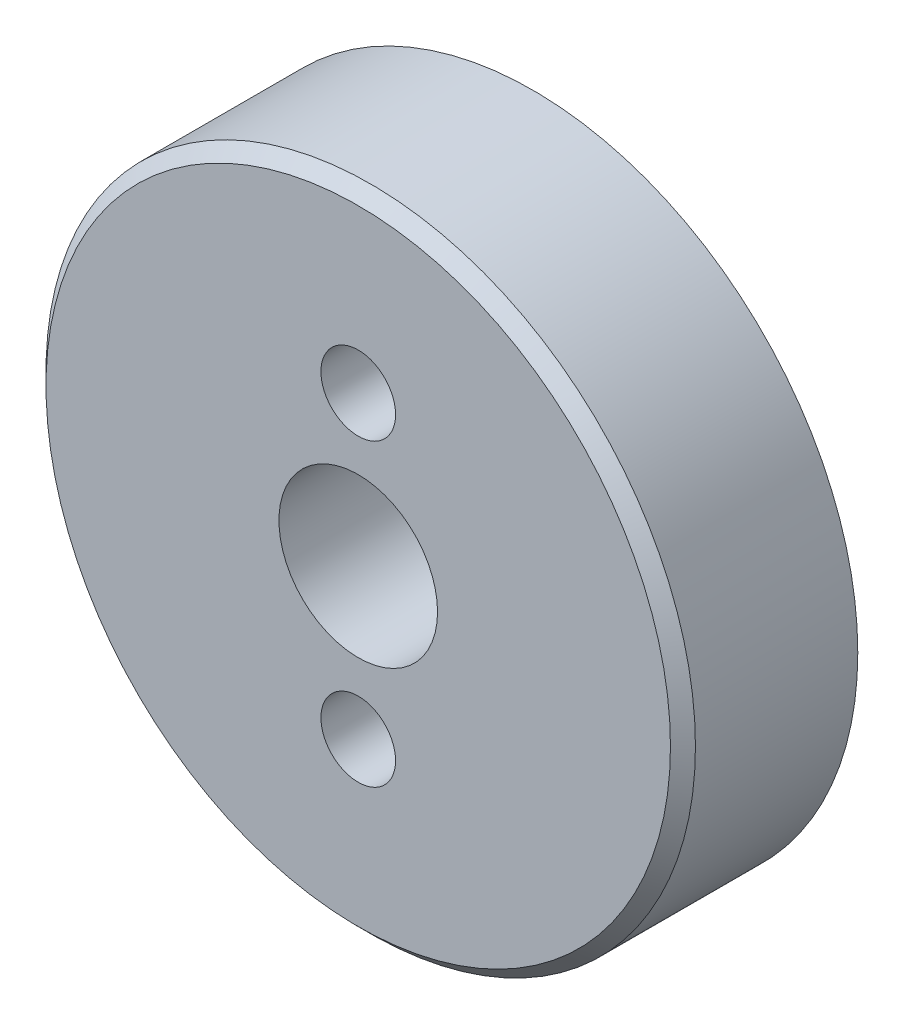
SolidWorks part; units mm, degrees
ref_plane "Спереди" through (0, 0, 0) normal (0, 0, 1) x (1, 0, 0)
ref_plane "Сверху" through (0, 0, 0) normal (0, 1, 0) x (1, 0, 0)
ref_plane "Справа" through (0, 0, 0) normal (1, 0, 0) x (0, 0, -1)
sketch "Эскиз1" plane through (0, 0, 0) normal (0, 0, 1) x (1, 0, 0)
  circle A0 centre (0, 0) radius 13
  circle A1 centre (0, 0) radius 3.175
  circle A2 centre (0, 6) radius 1.4944
  circle A3 centre (0, -6) radius 1.4944
  dimension "D1" = 6.35
  dimension "D2" = 26
  dimension "D3" = 6
extrude "Вытянуть1" add sketch "Эскиз1" along normal blind 7
chamfer "Фаска1" distance 0.5 angle 45 1 edges at (13, 0, 7)
